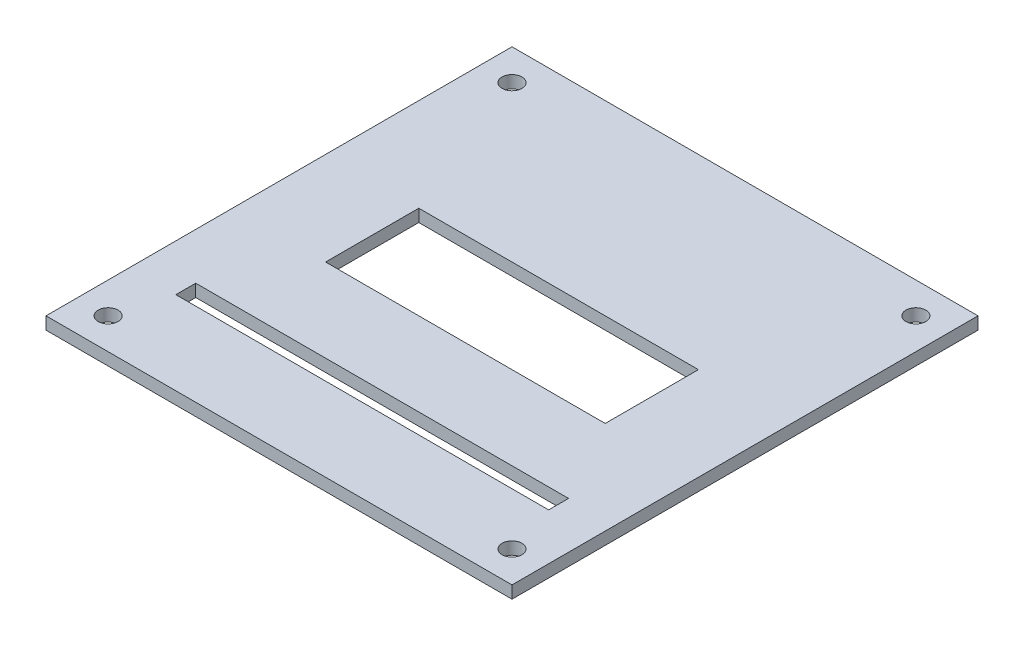
SolidWorks part; units mm, degrees
ref_plane "Front Plane" through (0, 0, 0) normal (0, 0, 1) x (1, 0, 0)
ref_plane "Top Plane" through (0, 0, 0) normal (0, 1, 0) x (1, 0, 0)
ref_plane "Right Plane" through (0, 0, 0) normal (1, 0, 0) x (0, 0, -1)
sketch "Sketch1" plane through (0, 0, 0) normal (0, 1, 0) x (1, 0, 0)
  line L0 (-37.5, 37.5) -> (-37.5, -37.5)
  line L1 (-32.5, 32.5) -> (32.5, 32.5)
  line L2 (-32.5, 32.5) -> (-32.5, -32.5)
  line L3 (-32.5, -32.5) -> (32.5, -32.5)
  line L4 (32.5, 32.5) -> (32.5, -32.5)
  line L5 (-32.5, 32.5) -> (32.5, -32.5) construction
  line L6 (-32.5, -32.5) -> (32.5, 32.5) construction
  line L7 (-37.5, -37.5) -> (37.5, -37.5)
  line L8 (37.5, 37.5) -> (37.5, -37.5)
  line L9 (-37.5, 37.5) -> (37.5, 37.5)
  circle A0 centre (-32.5, 32.5) radius 1.6
  circle A1 centre (-32.5, -32.5) radius 1.6
  circle A2 centre (32.5, 32.5) radius 1.6
  circle A3 centre (32.5, -32.5) radius 1.6
  point P0 (0, 0)
  dimension "D3" = 3.2
  dimension "D1" = 65
  dimension "D2" = 65
  dimension "D4" = 5
extrude "Boss-Extrude1" add sketch "Sketch1" along normal blind 2 contours A3 L4 A2 L1 A0 L2 A1 L3 | L9 L0 L7 L8 A3 L3 A1 L2 A0 L1 A2 L4
sketch "Sketch2" plane through (0, 0, 0) normal (0, -1, 0) x (1, 0, 0)
  line L1 (-22.5, 7.5) -> (22.5, 7.5)
  line L2 (-22.5, 7.5) -> (-22.5, -7.5)
  line L3 (-22.5, -7.5) -> (22.5, -7.5)
  line L4 (22.5, 7.5) -> (22.5, -7.5)
  line L5 (-22.5, 7.5) -> (22.5, -7.5) construction
  line L6 (-22.5, -7.5) -> (22.5, 7.5) construction
  point P0 (0, 0)
  dimension "D1" = 45
  dimension "D2" = 15
extrude "Cut-Extrude1" cut sketch "Sketch2" against normal blind 10
sketch "Sketch3" plane through (0, 0, 0) normal (0, -1, 0) x (1, 0, 0)
  line L0 (0, 37.5) -> (0, 7.5)
  line L1 (-37.5, 37.5) -> (37.5, 37.5) construction
  line L2 (22.5, 7.5) -> (-22.5, 7.5) construction
  line L4 (-30, 20.9) -> (30, 20.9)
  line L5 (-30, 20.9) -> (-30, 24.1)
  line L6 (-30, 24.1) -> (30, 24.1)
  line L7 (30, 20.9) -> (30, 24.1)
  line L8 (-30, 20.9) -> (30, 24.1) construction
  line L9 (-30, 24.1) -> (30, 20.9) construction
  point P6 (0, 22.5)
  dimension "D1" = 3.2
  dimension "D2" = 60
extrude "Cut-Extrude2" cut sketch "Sketch3" against normal blind 10 contours L6 L5 L4 L0 | L4 L7 L6 L0
